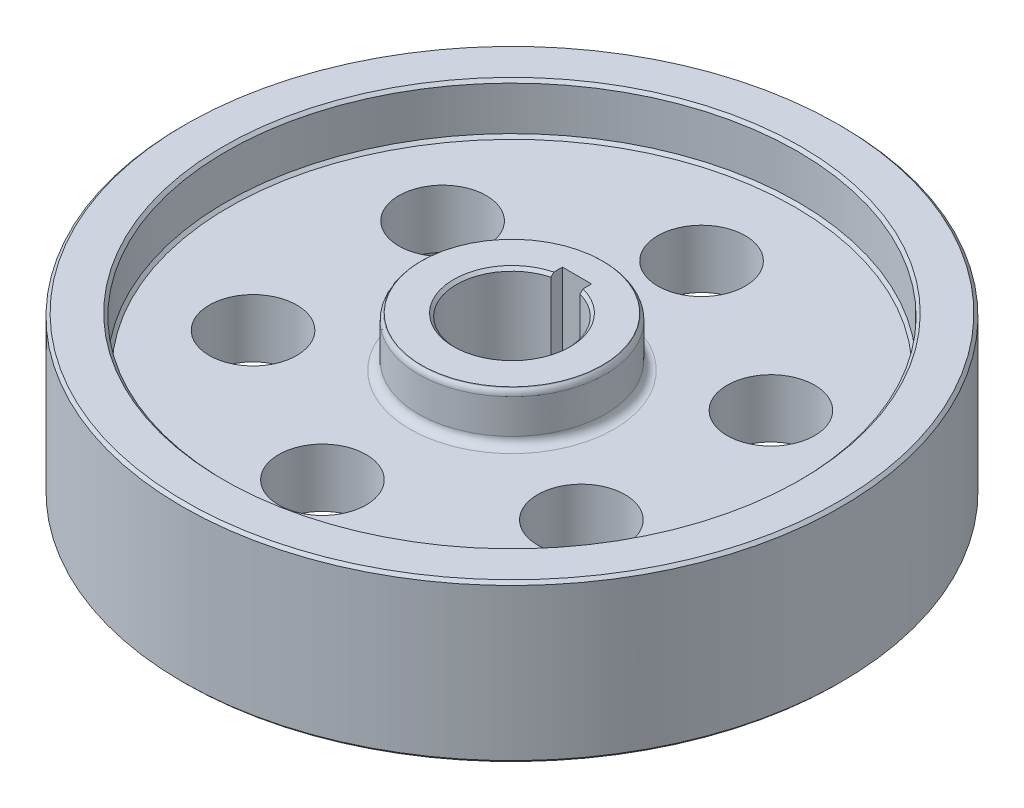
SolidWorks part; units mm, degrees
ref_plane "前视基准面" through (0, 0, 0) normal (0, 0, 1) x (1, 0, 0)
ref_plane "上视基准面" through (0, 0, 0) normal (0, 1, 0) x (1, 0, 0)
ref_plane "右视基准面" through (0, 0, 0) normal (1, 0, 0) x (0, 0, -1)
sketch "草图2" plane through (0, 0, 0) normal (1, 0, 0) x (0, 0, -1)
  line L0 (0, 0) -> (0, 18.342)
  line L1 (0, 18.342) -> (32, 18.342)
  line L2 (32, 18.342) -> (32, 1.342)
  line L3 (32, 1.342) -> (98, 1.342)
  line L4 (98, 1.342) -> (98, 18.342)
  line L5 (98, 18.342) -> (113, 18.342)
  line L6 (113, 18.342) -> (113, -13.3097)
  line L7 (98, -18.658) -> (32, -18.658)
  line L8 (0, -10.5375) -> (0, 0)
  line L9 (0, -10.5375) -> (0, -35.658)
  line L10 (0, -35.658) -> (32, -35.658)
  line L11 (32, -35.658) -> (32, -18.658)
  line L12 (98, -18.658) -> (98, -35.658)
  line L13 (98, -35.658) -> (113, -35.658)
  line L14 (113, -35.658) -> (113, -13.3097)
  dimension "D1" = 54
  dimension "D2" = 54
  dimension "D3" = 32
  dimension "D4" = 32
  dimension "D5" = 17
  dimension "D6" = 17
  dimension "D7" = 66
  dimension "D8" = 66
  dimension "D9" = 113
revolve "旋转1" add sketch "草图2" angle 360 about L9
sketch "草图3" plane through (0, 18.342, 0) normal (0, 1, 0) x (1, 0, 0)
  line L2 (-5, 18.3303) -> (-5, 22.3)
  line L3 (5, 18.3303) -> (5, 22.3)
  line L4 (-5, 22.3) -> (5, 22.3)
  arc A0 (-5, 18.3303) -> (5, 18.3303) centre (0, 0) ccw
  dimension "D1" = 38
  dimension "D4" = 22.3
extrude "切除-拉伸1" cut sketch "草图3" against normal through all
sketch "草图4" plane through (0, 1.342, 0) normal (0, 1, 0) x (1, 0, 0)
  circle A1 centre (0, 65) radius 15
  dimension "D2" = 30
extrude "切除-拉伸2" cut sketch "草图4" against normal through all
pattern_circular "阵列(圆周)1" count 6 over 360 about axis through (0, 0, 0) along (0, 1, 0) of "切除-拉伸2"
chamfer "倒角1" distance 1 angle 45 2 edges at (0, 18.342, 113) (0, -35.658, 113)
chamfer "倒角2" distance 1 angle 45 8 edges at (0, 18.342, 19) (0, 18.342, 32) (0, 1.342, 98) (0, 18.342, 98) (0, -35.658, 19) (0, -35.658, 32) (0, -18.658, 98) (0, -35.658, 98)
fillet "圆角1" radius 3 2 edges at (0, 1.342, 32) (0, 17.342, -32)
fillet "圆角2" radius 3 2 edges at (0, -18.658, 32) (0, -34.658, 32)
